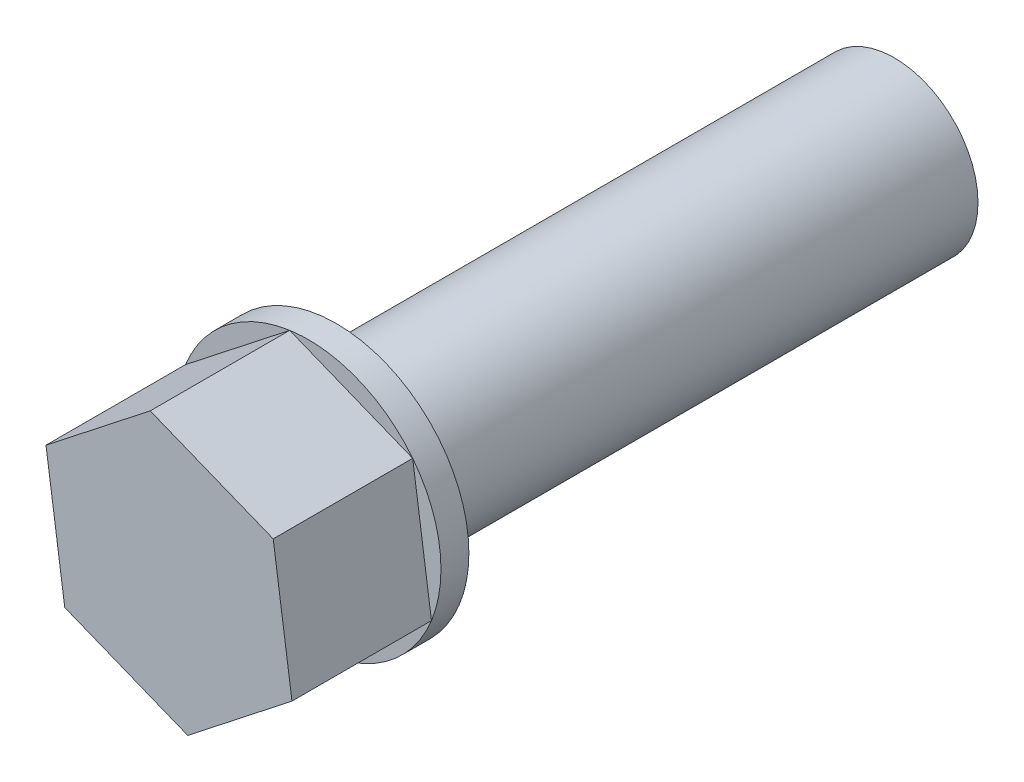
SolidWorks part; units mm, degrees
ref_plane "Alzado" through (0, 0, 0) normal (0, 0, 1) x (1, 0, 0)
ref_plane "Planta" through (0, 0, 0) normal (0, 1, 0) x (1, 0, 0)
ref_plane "Vista lateral" through (0, 0, 0) normal (1, 0, 0) x (0, 0, -1)
sketch "Croquis1" plane through (0, 0, 0) normal (0, 0, 1) x (1, 0, 0)
  circle A0 centre (0, 0) radius 6
extrude "Saliente-Extruir1" add sketch "Croquis1" along normal blind 40
sketch "Croquis2" plane through (0, 0, 40) normal (0, 0, 1) x (1, 0, 0)
  circle A0 centre (0, 0) radius 9.5
  dimension "D1" = 19
extrude "Saliente-Extruir2" add sketch "Croquis2" along normal blind 2
sketch "Croquis3" plane through (0, 0, 42) normal (0, 0, 1) x (1, 0, 0)
  line L1 (-1.3448, 9.4043) -> (-8.8168, 3.5376)
  line L2 (-8.8168, 3.5376) -> (-7.472, -5.8668)
  line L3 (-7.472, -5.8668) -> (1.3448, -9.4043)
  line L4 (1.3448, -9.4043) -> (8.8168, -3.5376)
  line L5 (8.8168, -3.5376) -> (7.472, 5.8668)
  line L6 (7.472, 5.8668) -> (-1.3448, 9.4043)
  circle A0 centre (0, 0) radius 8.2272 construction
extrude "Saliente-Extruir3" add sketch "Croquis3" along normal blind 10
